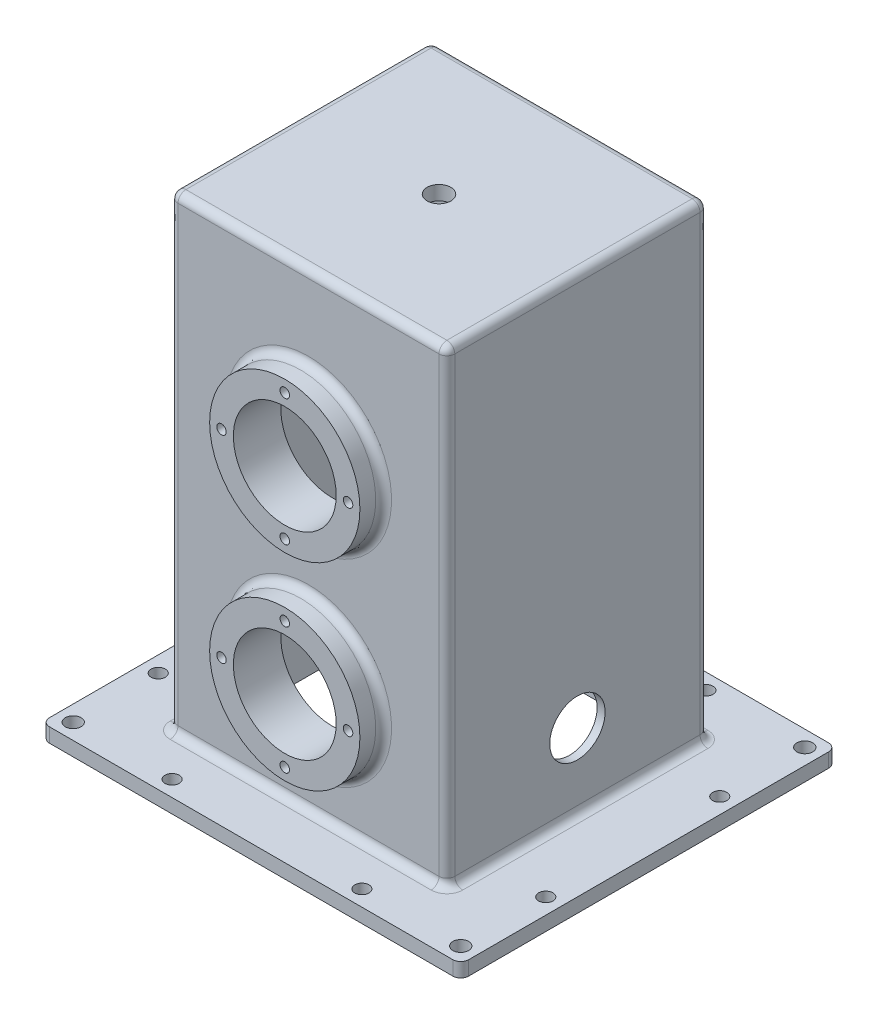
SolidWorks part; units mm, degrees
ref_plane "Front Plane" through (0, 0, 0) normal (0, 0, 1) x (1, 0, 0)
ref_plane "Top Plane" through (0, 0, 0) normal (0, 1, 0) x (1, 0, 0)
ref_plane "Right Plane" through (0, 0, 0) normal (1, 0, 0) x (0, 0, -1)
sketch "Sketch1" plane through (0, 0, 0) normal (0, 1, 0) x (1, 0, 0)
  line L1 (-265, -237.5) -> (265, -237.5)
  line L2 (-265, -237.5) -> (-265, 237.5)
  line L3 (-265, 237.5) -> (265, 237.5)
  line L4 (265, -237.5) -> (265, 237.5)
  line L5 (-265, -237.5) -> (265, 237.5) construction
  line L6 (-265, 237.5) -> (265, -237.5) construction
  point P0 (0, 0)
  dimension "D1" = 530
  dimension "D2" = 475
extrude "Boss-Extrude1" add sketch "Sketch1" along normal blind 18
sketch "Sketch2" plane through (0, 18, 0) normal (0, 1, 0) x (1, 0, 0)
  line L1 (-175, -165) -> (175, -165)
  line L2 (-175, -165) -> (-175, 165)
  line L3 (-175, 165) -> (175, 165)
  line L4 (175, -165) -> (175, 165)
  line L5 (-175, -165) -> (175, 165) construction
  line L6 (-175, 165) -> (175, -165) construction
  point P0 (0, 0)
  dimension "D1" = 350
  dimension "D2" = 330
extrude "Boss-Extrude2" add sketch "Sketch2" along normal blind 592
sketch "Sketch3" plane through (0, 0, 0) normal (0, -1, 0) x (1, 0, 0)
  line L1 (-165, 155) -> (165, 155)
  line L2 (-165, 155) -> (-165, -155)
  line L3 (-165, -155) -> (165, -155)
  line L4 (165, 155) -> (165, -155)
  line L5 (-165, 155) -> (165, -155) construction
  line L6 (-165, -155) -> (165, 155) construction
  point P0 (0, 0)
  dimension "D1" = 310
  dimension "D2" = 330
extrude "Cut-Extrude1" cut sketch "Sketch3" against normal blind 592
sketch "Sketch4" plane through (0, 0, 0) normal (0, -1, 0) x (1, 0, 0)
  line L0 (-245, 110) -> (-245, 217.5) construction
  line L1 (-245, 217.5) -> (-120, 217.5) construction
  line L3 (-265, 237.5) -> (265, 237.5) construction
  line L5 (-265, -237.5) -> (-265, 237.5) construction
  line L6 (0, 0) -> (60.812, 0) construction
  line L7 (0, 0) -> (0, 60.3442) construction
  circle A0 centre (-245, 217.5) radius 10
  circle A1 centre (-120, 217.5) radius 9
  circle A2 centre (-245, 110) radius 9
  circle A3 centre (245, 110) radius 9
  circle A4 centre (120, 217.5) radius 9
  circle A5 centre (245, 217.5) radius 10
  circle A6 centre (245, -110) radius 9
  circle A7 centre (245, -217.5) radius 10
  circle A8 centre (120, -217.5) radius 9
  circle A9 centre (-120, -217.5) radius 9
  circle A10 centre (-245, -217.5) radius 10
  circle A11 centre (-245, -110) radius 9
  dimension "D3" = 20
  dimension "D4" = 18
  dimension "D5" = 18
  dimension "D1" = 107.5
  dimension "D2" = 125
  dimension "D6" = 20
  dimension "D7" = 20
extrude "Cut-Extrude2" cut sketch "Sketch4" against normal through all
sketch "Sketch5" plane through (0, 0, 165) normal (0, 0, 1) x (1, 0, 0)
  line L0 (-265, 0) -> (265, 0) construction
  circle A0 centre (0, 410) radius 65
  circle A1 centre (0, 160) radius 65
  dimension "D1" = 130
  dimension "D2" = 130
  dimension "D3" = 160
  dimension "D4" = 250
extrude "Cut-Extrude3" cut sketch "Sketch5" against normal through all
sketch "Sketch6" plane through (0, 0, 165) normal (0, 0, 1) x (1, 0, 0)
  circle A0 centre (0, 410) radius 95
  circle A1 centre (0, 160) radius 95
  circle A2 centre (0, 410) radius 65
  circle A3 centre (0, 160) radius 65
  dimension "D1" = 190
  dimension "D2" = 190
extrude "Boss-Extrude4" add sketch "Sketch6" along normal mid plane 60
mirror "Mirror1" about plane through (0, 0, 0) normal (0, 0, 1) of "Boss-Extrude4"
sketch "Sketch8" plane through (0, 0, 195) normal (0, 0, 1) x (1, 0, 0)
  line L0 (0, 410) -> (0, 160) construction
  line L1 (0, 160) -> (0, 285) construction
  line L2 (0, 285) -> (-80, 285) construction
  circle A0 centre (0, 490) radius 6
  circle A1 centre (0, 410) radius 65 construction
  circle A2 centre (80, 410) radius 6
  circle A3 centre (0, 330) radius 6
  circle A4 centre (-80, 410) radius 6
  point P13 (0, 410)
  dimension "D1" = 12
  dimension "D2" = 80
  dimension "D3" = 4
extrude "Cut-Extrude5" cut sketch "Sketch8" against normal blind 42
sketch "Sketch9" plane through (0, 0, 195) normal (0, 0, 1) x (1, 0, 0)
  circle A0 centre (0, 240) radius 6
  circle A1 centre (0, 160) radius 65 construction
  circle A2 centre (80, 160) radius 6
  circle A3 centre (0, 80) radius 6
  circle A4 centre (-80, 160) radius 6
  point P13 (0, 160)
  dimension "D1" = 12
  dimension "D3" = 4
  dimension "D2" = 80
extrude "Cut-Extrude6" cut sketch "Sketch9" against normal blind 42
sketch "Sketch10" plane through (0, 610, 0) normal (0, 1, 0) x (1, 0, 0)
  circle A0 centre (0, 0) radius 15
  dimension "D1" = 30
extrude "Cut-Extrude7" cut sketch "Sketch10" against normal through all
sketch "Sketch11" plane through (175, 0, 0) normal (1, 0, 0) x (0, 0, -1)
  line L0 (-237.5, 0) -> (237.5, 0) construction
  circle A0 centre (0, 113) radius 35
  dimension "D1" = 70
  dimension "D2" = 113
extrude "Cut-Extrude8" cut sketch "Sketch11" against normal blind 42
fillet "Fillet1" radius 10 20 edges at (-95, 160, 165) (-95, 410, 165) (-175, 314, -165) (175, 314, -165) (-175, 314, 165) (175, 314, 165) (0, 610, -165) (175, 610, 0) (-175, 610, 0) (0, 610, 165) (-265, 9, -237.5) (265, 9, -237.5) (265, 9, 237.5) (-265, 9, 237.5) (-175, 18, 0) (0, 18, 165) (175, 18, 0) (0, 18, -165) (95, 160, -165) (95, 410, -165)
sketch "Sketch12" plane through (0, 0, -195) normal (0, 0, -1) x (-1, 0, 0)
  line L0 (0, 0) -> (0, 410) construction
  line L1 (0, 160) -> (65, 160) construction
  circle A0 centre (-0.0092, 240.0113) radius 6
  circle A1 centre (79.9908, 160.0113) radius 6
  circle A2 centre (-0.0092, 80.0113) radius 6
  circle A3 centre (-80.0092, 160.0113) radius 6
  circle A4 centre (0, 160) radius 65 construction
  circle A5 centre (0.0208, 489.9474) radius 6
  circle A6 centre (80.0208, 409.9474) radius 6
  circle A7 centre (0.0208, 329.9474) radius 6
  circle A8 centre (-79.9792, 409.9474) radius 6
  point P8 (-0.0092, 160.0113)
  point P13 (0, 0)
  point P27 (0.0208, 409.9474)
extrude "Cut-Extrude9" cut sketch "Sketch12" against normal blind 42
